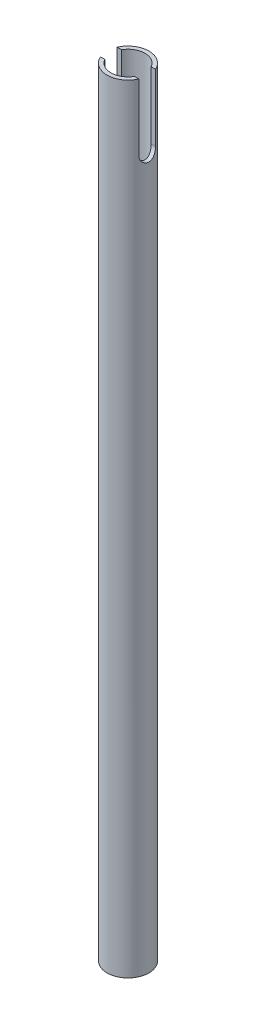
SolidWorks part; units mm, degrees
material "AISI 4130 Steel, annealed at 865C"
ref_plane "X-Y Datum" through (0, 0, 0) normal (0, 0, 1) x (1, 0, 0)
ref_plane "X-Z Datum" through (0, 0, 0) normal (0, 1, 0) x (1, 0, 0)
ref_plane "Y-Z Datum" through (0, 0, 0) normal (1, 0, 0) x (0, 0, -1)
sketch "Sketch1" plane through (0, 0, 0) normal (0, 1, 0) x (1, 0, 0)
  circle A0 centre (0, 0) radius 7.9375
  circle A1 centre (0, 0) radius 6.4643
  dimension "D1" = 15.875
  dimension "D2" = 1.4732
extrude "Boss-Extrude1" add sketch "Sketch1" along normal offset from surface (295.4744 mm away) 25.4
sketch "Sketch4" plane through (0, 0, 0) normal (1, 0, 0) x (0, 0, -1)
  line L5 (0, 320.8744) -> (0, 270.0744) construction
  line L7 (3.175, 320.8744) -> (3.175, 270.0744)
  line L8 (-3.175, 320.8744) -> (-3.175, 270.0744)
  arc A0 (3.175, 320.8744) -> (-3.175, 320.8744) centre (0, 320.8744) ccw
  arc A1 (-3.175, 270.0744) -> (3.175, 270.0744) centre (0, 270.0744) ccw
  point P4 (0, 295.4744)
  dimension "D1" = 6.35
  dimension "D2" = 25.4
extrude "Cut-Extrude1" cut sketch "Sketch4" against normal through all both and the other way through all
